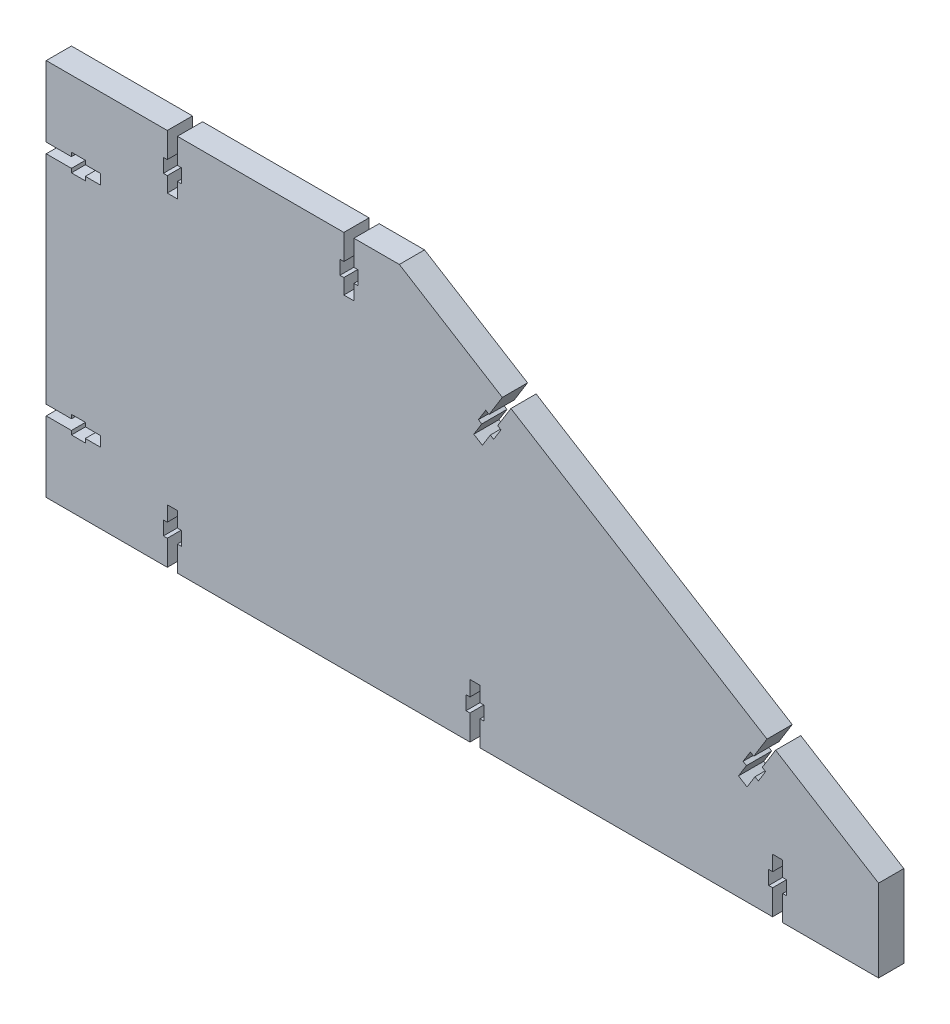
SolidWorks part; units mm, degrees
ref_plane "Plan de face" through (0, 0, 0) normal (0, 0, 1) x (1, 0, 0)
ref_plane "Plan de dessus" through (0, 0, 0) normal (0, 1, 0) x (1, 0, 0)
ref_plane "Plan de droite" through (0, 0, 0) normal (1, 0, 0) x (0, 0, -1)
sketch "Esquisse1" plane through (0, 0, 0) normal (0, 0, 1) x (1, 0, 0)
  line L0 (0, 0) -> (140, 0)
  line L1 (140, 0) -> (330, -117.4246)
  line L2 (330, -117.4246) -> (330, -150)
  line L3 (330, -150) -> (0, -150)
  line L4 (0, -150) -> (0, 0)
  dimension "D1" = 330
  dimension "D2" = 150
  dimension "D3" = 140
extrude "Boss.-Extru.1" add sketch "Esquisse1" along normal blind 10
sketch "Esquisse2" plane through (0, 0, 10) normal (0, 0, 1) x (1, 0, 0)
  line L0 (0, -28) -> (10, -28)
  line L1 (0, 0) -> (0, -150) construction
  line L2 (10, -28) -> (10, -26.45)
  line L3 (10, -26.45) -> (15.5, -26.45)
  line L4 (15.5, -26.45) -> (15.5, -28)
  line L5 (15.5, -28) -> (21.5, -28)
  line L6 (0, -28) -> (0, -32)
  line L7 (21.5, -28) -> (21.5, -32)
  line L8 (21.5, -30) -> (0, -30) construction
  line L9 (15.5, -32) -> (21.5, -32)
  line L10 (15.5, -33.55) -> (15.5, -32)
  line L11 (10, -33.55) -> (15.5, -33.55)
  line L12 (10, -32) -> (10, -33.55)
  line L13 (0, -32) -> (10, -32)
  line L14 (140, 0) -> (0, 0) construction
  line L15 (0, -75) -> (106.3611, -75) construction
  line L16 (0, -28) -> (10, -28)
  line L17 (10, -28) -> (10, -26.45)
  line L18 (10, -26.45) -> (15.5, -26.45)
  line L19 (15.5, -26.45) -> (15.5, -28)
  line L20 (15.5, -28) -> (21.5, -28)
  line L21 (15.5, -32) -> (21.5, -32)
  line L22 (15.5, -33.55) -> (15.5, -32)
  line L23 (10, -33.55) -> (15.5, -33.55)
  line L24 (10, -32) -> (10, -33.55)
  line L25 (0, -32) -> (10, -32)
  line L26 (21.5, -120) -> (0, -120) construction
  line L27 (0, -118) -> (10, -118)
  line L28 (10, -118) -> (10, -116.45)
  line L29 (10, -116.45) -> (15.5, -116.45)
  line L30 (15.5, -116.45) -> (15.5, -118)
  line L31 (15.5, -118) -> (21.5, -118)
  line L32 (15.5, -122) -> (21.5, -122)
  line L33 (15.5, -123.55) -> (15.5, -122)
  line L34 (10, -123.55) -> (15.5, -123.55)
  line L35 (10, -122) -> (10, -123.55)
  line L36 (0, -122) -> (10, -122)
  line L37 (0, -118) -> (10, -118)
  line L38 (10, -118) -> (10, -116.45)
  line L39 (10, -116.45) -> (15.5, -116.45)
  line L40 (15.5, -116.45) -> (15.5, -118)
  line L41 (15.5, -118) -> (21.5, -118)
  line L42 (21.5, -122) -> (21.5, -118)
  line L43 (0, -122) -> (0, -118)
  line L44 (15.5, -122) -> (21.5, -122)
  line L45 (15.5, -123.55) -> (15.5, -122)
  line L46 (10, -123.55) -> (15.5, -123.55)
  line L47 (10, -122) -> (10, -123.55)
  line L48 (0, -122) -> (10, -122)
  line L49 (168, -150) -> (168, -140)
  line L50 (48, -150) -> (48, -140)
  line L52 (48, -140) -> (46.45, -140)
  line L53 (46.45, -140) -> (46.45, -134.5)
  line L55 (46.45, -134.5) -> (48, -134.5)
  line L57 (48, -134.5) -> (48, -128.5)
  line L58 (52, -134.5) -> (52, -128.5)
  line L62 (53.55, -134.5) -> (52, -134.5)
  line L64 (53.55, -140) -> (53.55, -134.5)
  line L66 (52, -140) -> (53.55, -140)
  line L67 (52, -150) -> (52, -140)
  line L72 (48, -150) -> (48, -140)
  line L73 (48, -140) -> (46.45, -140)
  line L74 (46.45, -140) -> (46.45, -134.5)
  line L75 (46.45, -134.5) -> (48, -134.5)
  line L76 (48, -134.5) -> (48, -128.5)
  line L77 (52, -128.5) -> (48, -128.5)
  line L78 (52, -150) -> (48, -150)
  line L79 (52, -134.5) -> (52, -128.5)
  line L80 (53.55, -134.5) -> (52, -134.5)
  line L81 (53.55, -140) -> (53.55, -134.5)
  line L82 (52, -140) -> (53.55, -140)
  line L83 (52, -150) -> (52, -140)
  line L84 (0, -150) -> (330, -150) construction
  line L85 (168, -140) -> (166.45, -140)
  line L86 (166.45, -140) -> (166.45, -134.5)
  line L87 (166.45, -134.5) -> (168, -134.5)
  line L88 (168, -134.5) -> (168, -128.5)
  line L89 (172, -134.5) -> (172, -128.5)
  line L90 (173.55, -134.5) -> (172, -134.5)
  line L91 (173.55, -140) -> (173.55, -134.5)
  line L92 (172, -140) -> (173.55, -140)
  line L93 (172, -150) -> (172, -140)
  line L94 (168, -150) -> (168, -140)
  line L95 (168, -140) -> (166.45, -140)
  line L96 (166.45, -140) -> (166.45, -134.5)
  line L97 (166.45, -134.5) -> (168, -134.5)
  line L98 (168, -134.5) -> (168, -128.5)
  line L99 (172, -128.5) -> (168, -128.5)
  line L100 (172, -150) -> (168, -150)
  line L101 (172, -134.5) -> (172, -128.5)
  line L102 (173.55, -134.5) -> (172, -134.5)
  line L103 (173.55, -140) -> (173.55, -134.5)
  line L104 (172, -140) -> (173.55, -140)
  line L105 (172, -150) -> (172, -140)
  line L106 (288, -150) -> (288, -140)
  line L107 (288, -140) -> (286.45, -140)
  line L108 (286.45, -140) -> (286.45, -134.5)
  line L109 (286.45, -134.5) -> (288, -134.5)
  line L110 (288, -134.5) -> (288, -128.5)
  line L111 (292, -134.5) -> (292, -128.5)
  line L112 (293.55, -134.5) -> (292, -134.5)
  line L113 (293.55, -140) -> (293.55, -134.5)
  line L114 (292, -140) -> (293.55, -140)
  line L115 (292, -150) -> (292, -140)
  line L116 (288, -150) -> (288, -140)
  line L117 (288, -140) -> (286.45, -140)
  line L118 (286.45, -140) -> (286.45, -134.5)
  line L119 (286.45, -134.5) -> (288, -134.5)
  line L120 (288, -134.5) -> (288, -128.5)
  line L121 (292, -128.5) -> (288, -128.5)
  line L122 (292, -150) -> (288, -150)
  line L123 (292, -134.5) -> (292, -128.5)
  line L124 (293.55, -134.5) -> (292, -134.5)
  line L125 (293.55, -140) -> (293.55, -134.5)
  line L126 (292, -140) -> (293.55, -140)
  line L127 (292, -150) -> (292, -140)
  line M16 (0, 0) -> (0, -150)
  line M17 (0, -150) -> (330, -150)
  dimension "D1" = 10
  dimension "D2" = 5.5
  dimension "D3" = 6
  dimension "D4" = 2
  dimension "D5" = 2
  dimension "D6" = 7.1
  dimension "D7" = 30
  dimension "D8" = 0
  dimension "D9" = 6
  dimension "D10" = 10
  dimension "D11" = 5.5
  dimension "D12" = 4
  dimension "D13" = 7.1
  dimension "D14" = 4
  dimension "D15" = 48
  dimension "D16" = 3
extrude "Enlèv. mat.-Extru.1" cut sketch "Esquisse2" against normal blind 10 contours L58 L77 L57 L55 L53 L52 L50 L67 L66 L64 L62 M17 | L89 L99 L88 L87 L86 L85 L49 L93 L92 L91 L90 M17 | L111 L121 L110 L109 L108 L107 L106 L115 L114 L113 L112 M17 | L13 L12 L11 L10 L9 L7 L5 L4 L3 L2 L0 M16 | L32 L42 L31 L30 L29 L28 L27 L36 L35 L34 L33 M16
sketch "Esquisse3" plane through (0, 0, 10) normal (0, 0, 1) x (1, 0, 0)
  line L0 (48, 0) -> (48, -10)
  line L1 (140, 0) -> (0, 0) construction
  line L2 (48, -10) -> (46.45, -10)
  line L3 (46.45, -10) -> (46.45, -15.5)
  line L4 (46.45, -15.5) -> (48, -15.5)
  line L5 (48, -15.5) -> (48, -21.5)
  line L6 (48, -21.5) -> (52, -21.5)
  line L7 (50, -21.5) -> (50, 0) construction
  line L8 (52, -15.5) -> (52, -21.5)
  line L9 (53.55, -15.5) -> (52, -15.5)
  line L10 (53.55, -10) -> (53.55, -15.5)
  line L11 (52, -10) -> (53.55, -10)
  line L12 (52, 0) -> (52, -10)
  line L13 (118, 0) -> (118, -10)
  line L14 (0, 0) -> (0, -28) construction
  line L15 (118, -10) -> (116.45, -10)
  line L16 (116.45, -10) -> (116.45, -15.5)
  line L17 (116.45, -15.5) -> (118, -15.5)
  line L18 (118, -15.5) -> (118, -21.5)
  line L19 (118, -21.5) -> (122, -21.5)
  line L20 (122, -15.5) -> (122, -21.5)
  line L21 (123.55, -15.5) -> (122, -15.5)
  line L22 (123.55, -10) -> (123.55, -15.5)
  line L23 (122, -10) -> (123.55, -10)
  line L24 (122, 0) -> (122, -10)
  line L25 (120, -21.5) -> (120, 0) construction
  line L26 (118, 0) -> (122, 0)
  line L27 (48, 0) -> (52, 0)
  dimension "D1" = 10
  dimension "D2" = 5.5
  dimension "D3" = 6
  dimension "D4" = 4
  dimension "D5" = 4
  dimension "D6" = 7.1
  dimension "D7" = 50
  dimension "D8" = 2
extrude "Enlèv. mat.-Extru.2" cut sketch "Esquisse3" against normal blind 10 contours L26 L24 L23 L22 L21 L20 L19 L18 L17 L16 L15 L13 | L27 L12 L11 L10 L9 L8 L6 L5 L4 L3 L2 L0
sketch "Esquisse4" plane through (0, 0, 10) normal (0, 0, 1) x (1, 0, 0)
  line L0 (180.8314, -25.2348) -> (175.5742, -33.7413)
  line L1 (330, -117.4246) -> (140, 0) construction
  line L2 (175.5742, -33.7413) -> (174.2557, -32.9265)
  line L3 (174.2557, -32.9265) -> (171.3642, -37.6051)
  line L4 (171.3642, -37.6051) -> (172.6827, -38.4199)
  line L5 (172.6827, -38.4199) -> (169.5283, -43.5239)
  line L6 (169.5283, -43.5239) -> (172.931, -45.6268)
  line L7 (171.2296, -44.5753) -> (182.5327, -26.2862) construction
  line L8 (180.8314, -25.2348) -> (184.234, -27.3377)
  line L9 (176.0853, -40.5228) -> (172.931, -45.6268)
  line L10 (177.4038, -41.3377) -> (176.0853, -40.5228)
  line L11 (180.2953, -36.6591) -> (177.4038, -41.3377)
  line L12 (178.9768, -35.8442) -> (180.2953, -36.6591)
  line L13 (184.234, -27.3377) -> (178.9768, -35.8442)
  line L14 (285.766, -90.0869) -> (280.5087, -98.5934)
  line L15 (280.5087, -98.5934) -> (279.1902, -97.7785)
  line L16 (279.1902, -97.7785) -> (276.2987, -102.4571)
  line L17 (276.2987, -102.4571) -> (277.6172, -103.272)
  line L18 (277.6172, -103.272) -> (274.4629, -108.3759)
  line L19 (274.4629, -108.3759) -> (277.8655, -110.4788)
  line L20 (276.1642, -109.4274) -> (287.4673, -91.1383) construction
  line L21 (285.766, -90.0869) -> (289.1686, -92.1898)
  line L22 (281.0198, -105.3749) -> (277.8655, -110.4788)
  line L23 (282.3384, -106.1898) -> (281.0198, -105.3749)
  line L24 (285.2298, -101.5112) -> (282.3384, -106.1898)
  line L25 (283.9113, -100.6963) -> (285.2298, -101.5112)
  line L26 (289.1686, -92.1898) -> (283.9113, -100.6963)
  dimension "D1" = 2
  dimension "D2" = 2
  dimension "D3" = 5.5
  dimension "D4" = 10
  dimension "D5" = 6
  dimension "D6" = 7.1
  dimension "D7" = 50
  dimension "D8" = 2
  dimension "D9" = 2
  dimension "D10" = 5.5
  dimension "D11" = 10
  dimension "D12" = 6
  dimension "D13" = 7.1
  dimension "D14" = 50
extrude "Enlèv. mat.-Extru.3" cut sketch "Esquisse4" against normal blind 10
